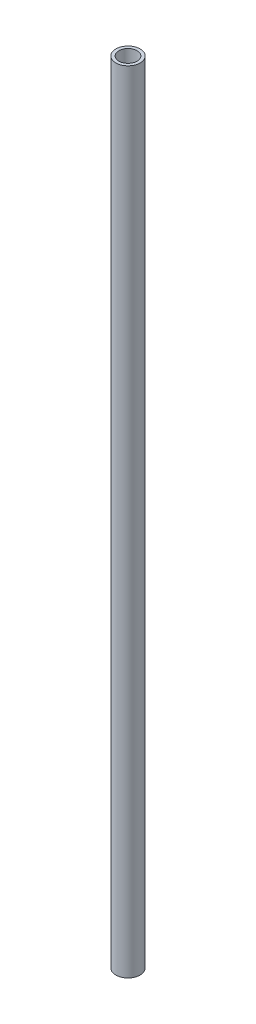
SolidWorks part; units mm, degrees
ref_plane "Front Plane" through (0, 0, 0) normal (0, 0, 1) x (1, 0, 0)
ref_plane "Top Plane" through (0, 0, 0) normal (0, 1, 0) x (1, 0, 0)
ref_plane "Right Plane" through (0, 0, 0) normal (1, 0, 0) x (0, 0, -1)
sketch "Sketch1" plane through (0, 0, 0) normal (0, 1, 0) x (1, 0, 0)
  circle A0 centre (0, 0) radius 0.75
  circle A1 centre (0, 0) radius 1
extrude "Boss-Extrude1" add sketch "Sketch1" along normal mid plane 65
